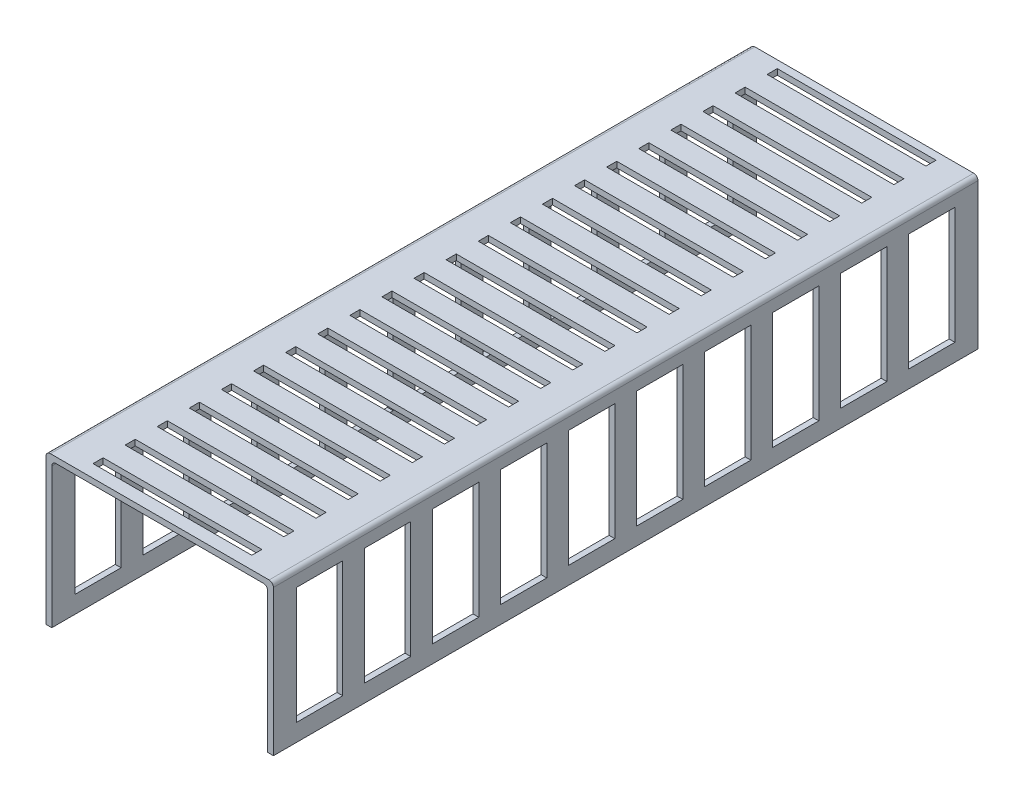
SolidWorks part; units mm, degrees
material "Nylon 101"
ref_plane "Front Plane" through (0, 0, 0) normal (0, 0, 1) x (1, 0, 0)
ref_plane "Top Plane" through (0, 0, 0) normal (0, 1, 0) x (1, 0, 0)
ref_plane "Right Plane" through (0, 0, 0) normal (1, 0, 0) x (0, 0, -1)
sketch "Sketch2" plane through (0, 27504.2493, 0) normal (0, 1, 0) x (1, 0, 0)
  line L0 (-34.7, 125.2786) -> (-34.7, 121.7786)
  line L5 (-34.7, 121.7786) -> (20.3, 121.7786)
  line L6 (-34.7, 125.2786) -> (20.3, 125.2786)
  line L7 (20.3, 125.2786) -> (20.3, 121.7786)
  line L9 (-46.6, 139.05) -> (32.2, 139.05)
  line L10 (-46.6, 139.05) -> (-46.6, -105.05)
  line L11 (-46.6, -105.05) -> (32.2, -105.05)
  line L12 (32.2, 139.05) -> (32.2, -105.05)
  line L13 (-49.2, -106.05) -> (34.8, -106.05) construction
  line L17 (33.2179, 134.65) -> (30.05, 134.65) construction
  line L18 (30.05, 129.75) -> (30.05, 135.7) construction
  line L19 (-38.7, 144.3) -> (-38.7, 136.4) construction
  line L20 (-34.7, 136.4) -> (20.3, 136.4)
  line L21 (-34.7, 136.4) -> (-34.7, 132.9)
  line L22 (-34.7, 132.9) -> (20.3, 132.9)
  line L23 (20.3, 136.4) -> (20.3, 132.9)
  line L24 (-34.7, 136.4) -> (20.3, 132.9) construction
  line L25 (-34.7, 132.9) -> (20.3, 136.4) construction
  line L26 (-34.7, 114.1571) -> (-34.7, 110.6571)
  line L27 (-34.7, 110.6571) -> (20.3, 110.6571)
  line L28 (-34.7, 114.1571) -> (20.3, 114.1571)
  line L29 (20.3, 114.1571) -> (20.3, 110.6571)
  line L30 (-34.7, 103.0357) -> (-34.7, 99.5357)
  line L31 (-34.7, 99.5357) -> (20.3, 99.5357)
  line L32 (-34.7, 103.0357) -> (20.3, 103.0357)
  line L33 (20.3, 103.0357) -> (20.3, 99.5357)
  line L34 (-34.7, 91.9143) -> (-34.7, 88.4143)
  line L35 (-34.7, 88.4143) -> (20.3, 88.4143)
  line L36 (-34.7, 91.9143) -> (20.3, 91.9143)
  line L37 (20.3, 91.9143) -> (20.3, 88.4143)
  line L38 (-34.7, 80.7929) -> (-34.7, 77.2929)
  line L39 (-34.7, 77.2929) -> (20.3, 77.2929)
  line L40 (-34.7, 80.7929) -> (20.3, 80.7929)
  line L41 (20.3, 80.7929) -> (20.3, 77.2929)
  line L42 (-34.7, 69.6714) -> (-34.7, 66.1714)
  line L43 (-34.7, 66.1714) -> (20.3, 66.1714)
  line L44 (-34.7, 69.6714) -> (20.3, 69.6714)
  line L45 (20.3, 69.6714) -> (20.3, 66.1714)
  line L46 (-34.7, 58.55) -> (-34.7, 55.05)
  line L47 (-34.7, 55.05) -> (20.3, 55.05)
  line L48 (-34.7, 58.55) -> (20.3, 58.55)
  line L49 (20.3, 58.55) -> (20.3, 55.05)
  line L50 (-34.7, 47.4286) -> (-34.7, 43.9286)
  line L51 (-34.7, 43.9286) -> (20.3, 43.9286)
  line L52 (-34.7, 47.4286) -> (20.3, 47.4286)
  line L53 (20.3, 47.4286) -> (20.3, 43.9286)
  line L54 (-34.7, 36.3071) -> (-34.7, 32.8071)
  line L55 (-34.7, 32.8071) -> (20.3, 32.8071)
  line L56 (-34.7, 36.3071) -> (20.3, 36.3071)
  line L57 (20.3, 36.3071) -> (20.3, 32.8071)
  line L58 (-34.7, 25.1857) -> (-34.7, 21.6857)
  line L59 (-34.7, 21.6857) -> (20.3, 21.6857)
  line L60 (-34.7, 25.1857) -> (20.3, 25.1857)
  line L61 (20.3, 25.1857) -> (20.3, 21.6857)
  line L62 (-34.7, 14.0643) -> (-34.7, 10.5643)
  line L63 (-34.7, 10.5643) -> (20.3, 10.5643)
  line L64 (-34.7, 14.0643) -> (20.3, 14.0643)
  line L65 (20.3, 14.0643) -> (20.3, 10.5643)
  line L66 (-34.7, 2.9429) -> (-34.7, -0.5571)
  line L67 (-34.7, -0.5571) -> (20.3, -0.5571)
  line L68 (-34.7, 2.9429) -> (20.3, 2.9429)
  line L69 (20.3, 2.9429) -> (20.3, -0.5571)
  line L70 (-34.7, -8.1786) -> (-34.7, -11.6786)
  line L71 (-34.7, -11.6786) -> (20.3, -11.6786)
  line L72 (-34.7, -8.1786) -> (20.3, -8.1786)
  line L73 (20.3, -8.1786) -> (20.3, -11.6786)
  line L74 (-34.7, -19.3) -> (-34.7, -22.8)
  line L75 (-34.7, -22.8) -> (20.3, -22.8)
  line L76 (-34.7, -19.3) -> (20.3, -19.3)
  line L77 (20.3, -19.3) -> (20.3, -22.8)
  line L78 (-34.7, -30.4214) -> (-34.7, -33.9214)
  line L79 (-34.7, -33.9214) -> (20.3, -33.9214)
  line L80 (-34.7, -30.4214) -> (20.3, -30.4214)
  line L81 (20.3, -30.4214) -> (20.3, -33.9214)
  line L82 (-34.7, -41.5429) -> (-34.7, -45.0429)
  line L83 (-34.7, -45.0429) -> (20.3, -45.0429)
  line L84 (-34.7, -41.5429) -> (20.3, -41.5429)
  line L85 (20.3, -41.5429) -> (20.3, -45.0429)
  line L86 (-34.7, -52.6643) -> (-34.7, -56.1643)
  line L87 (-34.7, -56.1643) -> (20.3, -56.1643)
  line L88 (-34.7, -52.6643) -> (20.3, -52.6643)
  line L89 (20.3, -52.6643) -> (20.3, -56.1643)
  line L90 (-34.7, -63.7857) -> (-34.7, -67.2857)
  line L91 (-34.7, -67.2857) -> (20.3, -67.2857)
  line L92 (-34.7, -63.7857) -> (20.3, -63.7857)
  line L93 (20.3, -63.7857) -> (20.3, -67.2857)
  line L94 (-34.7, -74.9071) -> (-34.7, -78.4071)
  line L95 (-34.7, -78.4071) -> (20.3, -78.4071)
  line L96 (-34.7, -74.9071) -> (20.3, -74.9071)
  line L97 (20.3, -74.9071) -> (20.3, -78.4071)
  line L98 (-34.7, -86.0286) -> (-34.7, -89.5286)
  line L99 (-34.7, -89.5286) -> (20.3, -89.5286)
  line L100 (-34.7, -86.0286) -> (20.3, -86.0286)
  line L101 (20.3, -86.0286) -> (20.3, -89.5286)
  line L102 (-34.7, -97.15) -> (-34.7, -100.65)
  line L103 (-34.7, -100.65) -> (20.3, -100.65)
  line L104 (-34.7, -97.15) -> (20.3, -97.15)
  line L105 (20.3, -97.15) -> (20.3, -100.65)
  line L107 (-49.2, 140.05) -> (34.8, 140.05) construction
  line L108 (-47.2, -105.65) -> (-47.2, 139.65) construction
  line L109 (32.8, -105.65) -> (32.8, 139.65) construction
  point P21 (-7.2, 134.65)
  dimension "D1" = 1
  dimension "D2" = 1
  dimension "D3" = 0.6
  dimension "D4" = 0.6
  dimension "D5" = 4
  dimension "D6" = 3.5
  dimension "D8" = 4.4
  dimension "D9" = 4.4
  dimension "D7" = 22
extrude "Boss-Extrude1" add sketch "Sketch2" along normal blind 2
sketch "Sketch3" plane through (0, 27504.2493, 0) normal (0, -1, 0) x (1, 0, 0)
  line L0 (32.2, -139.05) -> (-46.6, -139.05) construction
  line L1 (-46.6, 105.05) -> (-44.6, 105.05)
  line L2 (-46.6, 105.05) -> (-46.6, -139.05)
  line L3 (-46.6, -139.05) -> (-44.6, -139.05)
  line L4 (-44.6, 105.05) -> (-44.6, -139.05)
  line L5 (-7.2, 105.05) -> (-7.2, -2.7153) construction
  line L6 (-46.6, 105.05) -> (32.2, 105.05) construction
  line L7 (30.2, 105.05) -> (30.2, -139.05)
  line L8 (32.2, -139.05) -> (30.2, -139.05)
  line L9 (32.2, 105.05) -> (32.2, -139.05)
  line L10 (32.2, 105.05) -> (30.2, 105.05)
  dimension "D1" = 2
extrude "Boss-Extrude2" add sketch "Sketch3" along normal blind 50
fillet "Fillet1" radius 1.5 4 edges at (-44.6, 27504.2493, -17) (-46.6, 27506.2493, -17) (30.2, 27504.2493, -17) (32.2, 27506.2493, -17)
sketch "Sketch4" plane through (32.2, 0, 0) normal (1, 0, 0) x (0, 0, -1)
  line L0 (-105.05, 27504.7493) -> (-105.05, 27454.2493) construction
  line L1 (-97.05, 27500.7493) -> (-81.05, 27500.7493)
  line L2 (-97.05, 27500.7493) -> (-97.05, 27460.2493)
  line L3 (-97.05, 27460.2493) -> (-81.05, 27460.2493)
  line L4 (-81.05, 27500.7493) -> (-81.05, 27460.2493)
  line L5 (139.05, 27504.7493) -> (-105.05, 27504.7493) construction
  line L6 (139.05, 27454.2493) -> (-105.05, 27454.2493) construction
  line L7 (-73.4833, 27500.7493) -> (-57.4833, 27500.7493)
  line L8 (-73.4833, 27500.7493) -> (-73.4833, 27460.2493)
  line L9 (-73.4833, 27460.2493) -> (-57.4833, 27460.2493)
  line L10 (-57.4833, 27500.7493) -> (-57.4833, 27460.2493)
  line L11 (-49.9167, 27500.7493) -> (-33.9167, 27500.7493)
  line L12 (-49.9167, 27500.7493) -> (-49.9167, 27460.2493)
  line L13 (-49.9167, 27460.2493) -> (-33.9167, 27460.2493)
  line L14 (-33.9167, 27500.7493) -> (-33.9167, 27460.2493)
  line L15 (-26.35, 27500.7493) -> (-10.35, 27500.7493)
  line L16 (-26.35, 27500.7493) -> (-26.35, 27460.2493)
  line L17 (-26.35, 27460.2493) -> (-10.35, 27460.2493)
  line L18 (-10.35, 27500.7493) -> (-10.35, 27460.2493)
  line L19 (-2.7833, 27500.7493) -> (13.2167, 27500.7493)
  line L20 (-2.7833, 27500.7493) -> (-2.7833, 27460.2493)
  line L21 (-2.7833, 27460.2493) -> (13.2167, 27460.2493)
  line L22 (13.2167, 27500.7493) -> (13.2167, 27460.2493)
  line L23 (20.7833, 27500.7493) -> (36.7833, 27500.7493)
  line L24 (20.7833, 27500.7493) -> (20.7833, 27460.2493)
  line L25 (20.7833, 27460.2493) -> (36.7833, 27460.2493)
  line L26 (36.7833, 27500.7493) -> (36.7833, 27460.2493)
  line L27 (44.35, 27500.7493) -> (60.35, 27500.7493)
  line L28 (44.35, 27500.7493) -> (44.35, 27460.2493)
  line L29 (44.35, 27460.2493) -> (60.35, 27460.2493)
  line L30 (60.35, 27500.7493) -> (60.35, 27460.2493)
  line L31 (67.9167, 27500.7493) -> (83.9167, 27500.7493)
  line L32 (67.9167, 27500.7493) -> (67.9167, 27460.2493)
  line L33 (67.9167, 27460.2493) -> (83.9167, 27460.2493)
  line L34 (83.9167, 27500.7493) -> (83.9167, 27460.2493)
  line L35 (91.4833, 27500.7493) -> (107.4833, 27500.7493)
  line L36 (91.4833, 27500.7493) -> (91.4833, 27460.2493)
  line L37 (91.4833, 27460.2493) -> (107.4833, 27460.2493)
  line L38 (107.4833, 27500.7493) -> (107.4833, 27460.2493)
  line L39 (115.05, 27500.7493) -> (131.05, 27500.7493)
  line L40 (115.05, 27500.7493) -> (115.05, 27460.2493)
  line L41 (115.05, 27460.2493) -> (131.05, 27460.2493)
  line L42 (131.05, 27500.7493) -> (131.05, 27460.2493)
  line L43 (139.05, 27504.7493) -> (139.05, 27454.2493) construction
  dimension "D1" = 8
  dimension "D2" = 4
  dimension "D3" = 6
  dimension "D4" = 16
  dimension "D6" = 8
  dimension "D5" = 10
extrude "Cut-Extrude1" cut sketch "Sketch4" against normal through all
